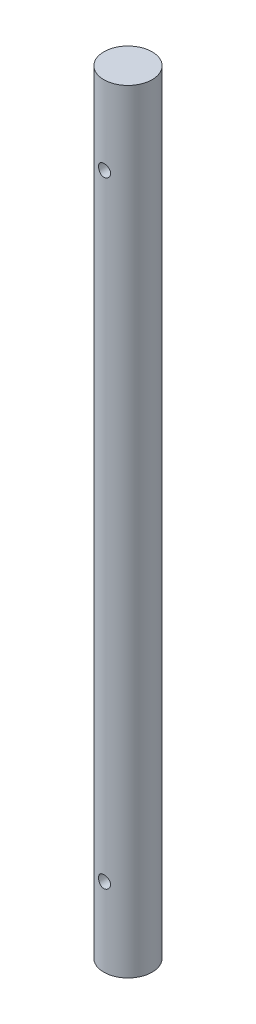
SolidWorks part; units mm, degrees
ref_plane "Front Plane" through (0, 0, 0) normal (0, 0, 1) x (1, 0, 0)
ref_plane "Top Plane" through (0, 0, 0) normal (0, 1, 0) x (1, 0, 0)
ref_plane "Right Plane" through (0, 0, 0) normal (1, 0, 0) x (0, 0, -1)
sketch "Sketch1" plane through (0, 0, 0) normal (0, 1, 0) x (1, 0, 0)
  circle A0 centre (0, 0) radius 6.35
  dimension "D1" = 12.7
extrude "Boss-Extrude1" add sketch "Sketch1" along normal blind 203.2
sketch "Sketch2" plane through (0, 0, 0) normal (0, 0, 1) x (1, 0, 0)
  line L0 (0, -6.985) -> (0, 6.985) construction
  line L1 (6.35, 203.2) -> (-6.35, 203.2) construction
  line L2 (6.985, 0) -> (-6.985, 0) construction
  circle A0 centre (0, 182.5625) radius 1.5875
  circle A1 centre (0, 20.6375) radius 1.5875
  dimension "D1" = 3.175
  dimension "D2" = 20.6375
  dimension "D3" = 20.6375
extrude "Cut-Extrude1" cut sketch "Sketch2" against normal through all both and the other way through all
equation "\"D3@Sketch2\"=\"D2@Sketch2\""
